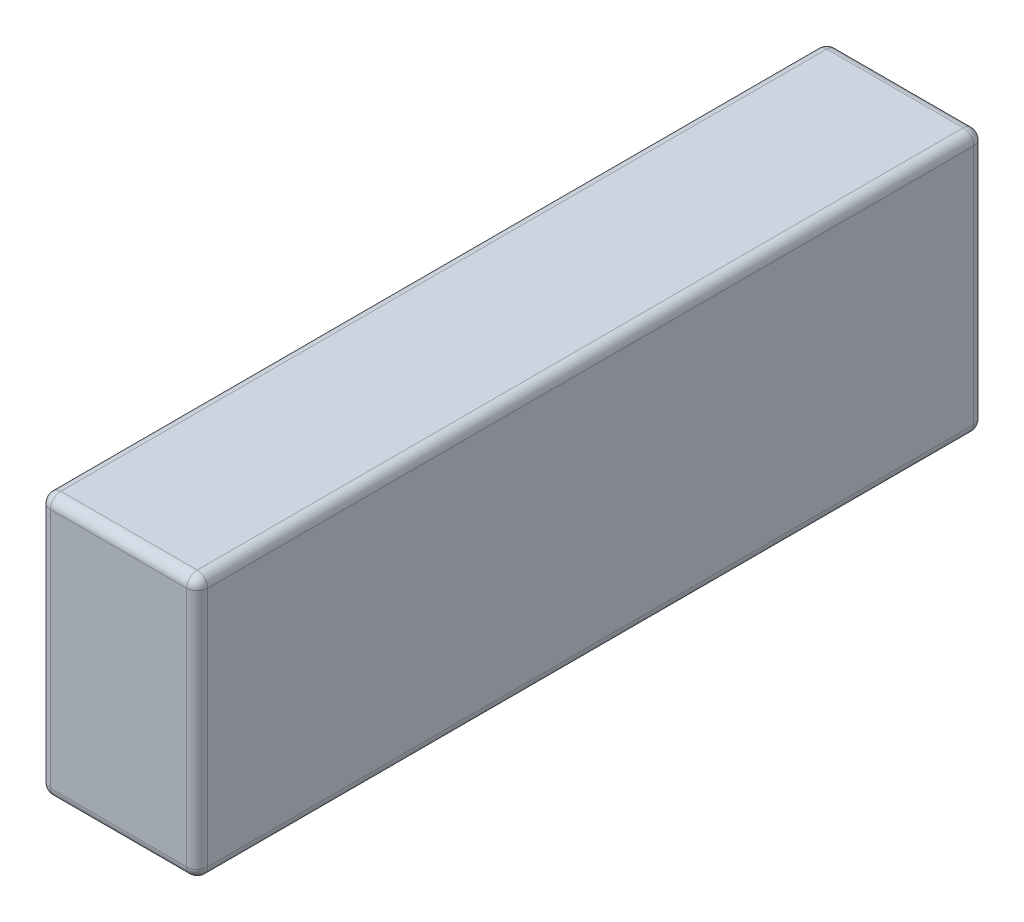
SolidWorks part; units mm, degrees
ref_plane "Front Plane" through (0, 0, 0) normal (0, 0, 1) x (1, 0, 0)
ref_plane "Top Plane" through (0, 0, 0) normal (0, 1, 0) x (1, 0, 0)
ref_plane "Right Plane" through (0, 0, 0) normal (1, 0, 0) x (0, 0, -1)
sketch "Sketch2" plane through (0, 0, 0) normal (1, 0, 0) x (0, 0, -1)
  line L1 (-7.5, 2.5) -> (7.5, 2.5)
  line L2 (-7.5, 2.5) -> (-7.5, -2.5)
  line L3 (-7.5, -2.5) -> (7.5, -2.5)
  line L4 (7.5, 2.5) -> (7.5, -2.5)
  line L5 (-7.5, 2.5) -> (7.5, -2.5) construction
  line L6 (-7.5, -2.5) -> (7.5, 2.5) construction
  point P0 (0, 0)
  dimension "D1" = 15
  dimension "D2" = 5
extrude "Boss-Extrude1" add sketch "Sketch2" along normal blind 3
fillet "Fillet1" radius 0.2 12 edges at (0, 0, 7.5) (1.5, -2.5, 7.5) (0, -2.5, 0) (1.5, -2.5, -7.5) (0, 0, -7.5) (3, -2.5, 0) (3, 0, -7.5) (3, 0, 7.5) (1.5, 2.5, 7.5) (0, 2.5, 0) (1.5, 2.5, -7.5) (3, 2.5, 0)
